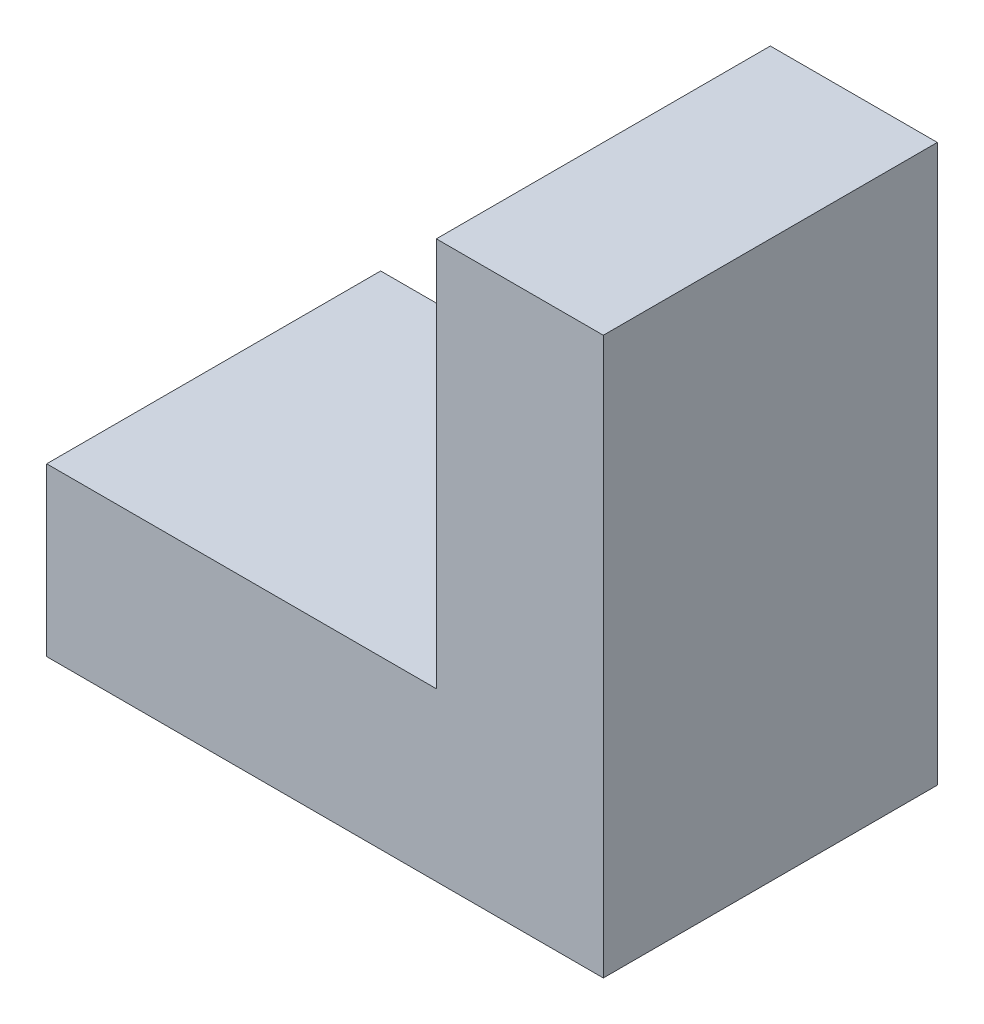
SolidWorks part; units mm, degrees
ref_plane "Спереди" through (0, 0, 0) normal (0, 0, 1) x (1, 0, 0)
ref_plane "Сверху" through (0, 0, 0) normal (0, 1, 0) x (1, 0, 0)
ref_plane "Справа" through (0, 0, 0) normal (1, 0, 0) x (0, 0, -1)
other "Configuration Table"
sketch "Эскиз1" plane through (0, 0, 0) normal (0, 0, 1) x (1, 0, 0)
  line L0 (-10, 0) -> (10, 0)
  line L1 (10, 0) -> (10, 20)
  line L2 (10, 20) -> (4, 20)
  line L3 (4, 20) -> (4, 6)
  line L4 (4, 6) -> (-10, 6)
  line L5 (-10, 6) -> (-10, 0)
extrude "12_Corner_cleat" add sketch "Эскиз1" along normal blind 12
